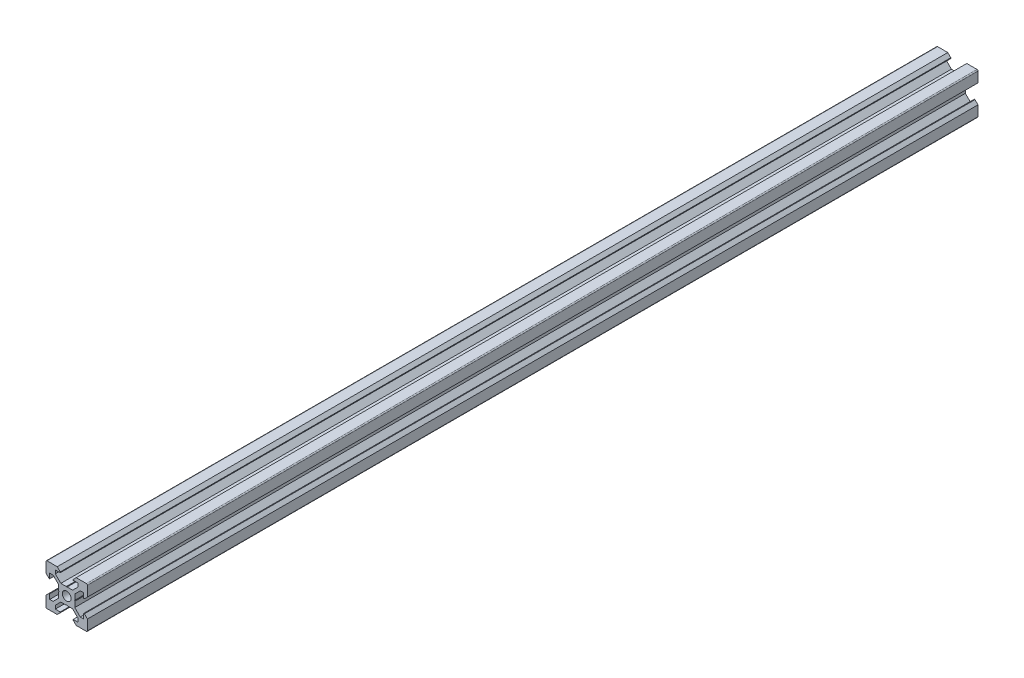
SolidWorks part; units mm, degrees
material "6061-T6 (SS)"
ref_plane "Front Plane" through (0, 0, 0) normal (0, 0, 1) x (1, 0, 0)
ref_plane "Top Plane" through (0, 0, 0) normal (0, 1, 0) x (1, 0, 0)
ref_plane "Right Plane" through (0, 0, 0) normal (1, 0, 0) x (0, 0, -1)
sketch "Sketch1" plane through (0, 0, 0) normal (0, 0, 1) x (1, 0, 0)
  line L1 (9.5, -10) -> (-9.5, -10)
  line L2 (10, -9.5) -> (10, 9.5)
  line L3 (9.5, 10) -> (-9.5, 10)
  line L4 (-10, -9.5) -> (-10, 9.5)
  line L5 (10, -10) -> (-10, 10) construction
  line L6 (10, 10) -> (-10, -10) construction
  circle A0 centre (0, 0) radius 2.1
  arc A1 (-9.5, 10) -> (-10, 9.5) centre (-9.5, 9.5) ccw
  arc A2 (10, 9.5) -> (9.5, 10) centre (9.5, 9.5) ccw
  arc A3 (9.5, -10) -> (10, -9.5) centre (9.5, -9.5) ccw
  arc A4 (-9.5, -10) -> (-10, -9.5) centre (-9.5, -9.5) cw
  point P0 (0, 0)
  line B0 (0, 0) -> (0, 10) construction
  line B1 (0, 3.69) -> (-0.21, 3.9)
  line B2 (-0.21, 3.9) -> (-2.8393, 3.9)
  line B3 (-2.8393, 3.9) -> (-5.5, 6.5607)
  line B4 (-5.5, 6.5607) -> (-5.5, 8.2)
  line B5 (-5.5, 8.2) -> (-3.125, 8.2)
  line B6 (-3.125, 8.2) -> (-3.125, 8.545)
  line B7 (-3.125, 8.545) -> (-4.58, 10)
  line B8 (-4.58, 10) -> (4.58, 10)
  line B9 (0, 0) -> (-5.9132, 5.9132) construction
  line B10 (3.125, 8.545) -> (4.58, 10)
  line B11 (3.125, 8.2) -> (3.125, 8.545)
  line B12 (5.5, 8.2) -> (3.125, 8.2)
  line B13 (5.5, 6.5607) -> (5.5, 8.2)
  line B14 (2.8393, 3.9) -> (5.5, 6.5607)
  line B15 (0.21, 3.9) -> (2.8393, 3.9)
  line B16 (0, 3.69) -> (0.21, 3.9)
  line B17 (0, 0) -> (-10, 0) construction
  line B18 (-3.69, 0) -> (-3.9, -0.21)
  line B19 (-3.9, -0.21) -> (-3.9, -2.8393)
  line B20 (-3.9, -2.8393) -> (-6.5607, -5.5)
  line B21 (-6.5607, -5.5) -> (-8.2, -5.5)
  line B22 (-8.2, -5.5) -> (-8.2, -3.125)
  line B23 (-8.2, -3.125) -> (-8.545, -3.125)
  line B24 (-8.545, -3.125) -> (-10, -4.58)
  line B25 (-10, -4.58) -> (-10, 4.58)
  line B26 (0, 0) -> (-5.9132, -5.9132) construction
  line B27 (-8.545, 3.125) -> (-10, 4.58)
  line B28 (-8.2, 3.125) -> (-8.545, 3.125)
  line B29 (-8.2, 5.5) -> (-8.2, 3.125)
  line B30 (-6.5607, 5.5) -> (-8.2, 5.5)
  line B31 (-3.9, 2.8393) -> (-6.5607, 5.5)
  line B32 (-3.9, 0.21) -> (-3.9, 2.8393)
  line B33 (-3.69, 0) -> (-3.9, 0.21)
  line B34 (0, 0) -> (0, -10) construction
  line B35 (0, -3.69) -> (0.21, -3.9)
  line B36 (0.21, -3.9) -> (2.8393, -3.9)
  line B37 (2.8393, -3.9) -> (5.5, -6.5607)
  line B38 (5.5, -6.5607) -> (5.5, -8.2)
  line B39 (5.5, -8.2) -> (3.125, -8.2)
  line B40 (3.125, -8.2) -> (3.125, -8.545)
  line B41 (3.125, -8.545) -> (4.58, -10)
  line B42 (4.58, -10) -> (-4.58, -10)
  line B43 (0, 0) -> (5.9132, -5.9132) construction
  line B44 (-3.125, -8.545) -> (-4.58, -10)
  line B45 (-3.125, -8.2) -> (-3.125, -8.545)
  line B46 (-5.5, -8.2) -> (-3.125, -8.2)
  line B47 (-5.5, -6.5607) -> (-5.5, -8.2)
  line B48 (-2.8393, -3.9) -> (-5.5, -6.5607)
  line B49 (-0.21, -3.9) -> (-2.8393, -3.9)
  line B50 (0, -3.69) -> (-0.21, -3.9)
  line B51 (0, 0) -> (10, 0) construction
  line B52 (3.69, 0) -> (3.9, 0.21)
  line B53 (3.9, 0.21) -> (3.9, 2.8393)
  line B54 (3.9, 2.8393) -> (6.5607, 5.5)
  line B55 (6.5607, 5.5) -> (8.2, 5.5)
  line B56 (8.2, 5.5) -> (8.2, 3.125)
  line B57 (8.2, 3.125) -> (8.545, 3.125)
  line B58 (8.545, 3.125) -> (10, 4.58)
  line B59 (10, 4.58) -> (10, -4.58)
  line B60 (0, 0) -> (5.9132, 5.9132) construction
  line B61 (8.545, -3.125) -> (10, -4.58)
  line B62 (8.2, -3.125) -> (8.545, -3.125)
  line B63 (8.2, -5.5) -> (8.2, -3.125)
  line B64 (6.5607, -5.5) -> (8.2, -5.5)
  line B65 (3.9, -2.8393) -> (6.5607, -5.5)
  line B66 (3.9, -0.21) -> (3.9, -2.8393)
  line B67 (3.69, 0) -> (3.9, -0.21)
  dimension "D1" = 4.2
  dimension "D3" = 0.5
  dimension "D2" = 20
sketch_block_instance "V Slot 1-4"
sketch_block "V Slot 1" parameters "D1"=10, "D2"=11, "D3"=4.3, "D4"=1.8, "D5"=0.21, "D6"=45, "D7"=9.16, "D8"=1.5, "D9"=6.25
sketch_block_instance "V Slot 1-5"
sketch_block_instance "V Slot 1-6"
sketch_block_instance "V Slot 1-7"
extrude "Boss-Extrude1" add sketch "Sketch1" along normal blind 430 contours B67 B52 B53 B54 B55 B56 B57 B58 L2 A2 L3 B10 B11 B12 B13 B14 B15 B16 B1 B2 B3 B4 B5 B6 B7 A1 L4 B27 B28 B29 B30 B31 B32 B33 B18 B19 B20 B21 B22 B23 B24 A4 L1 B44 B45 B46 B47 B48 B49
